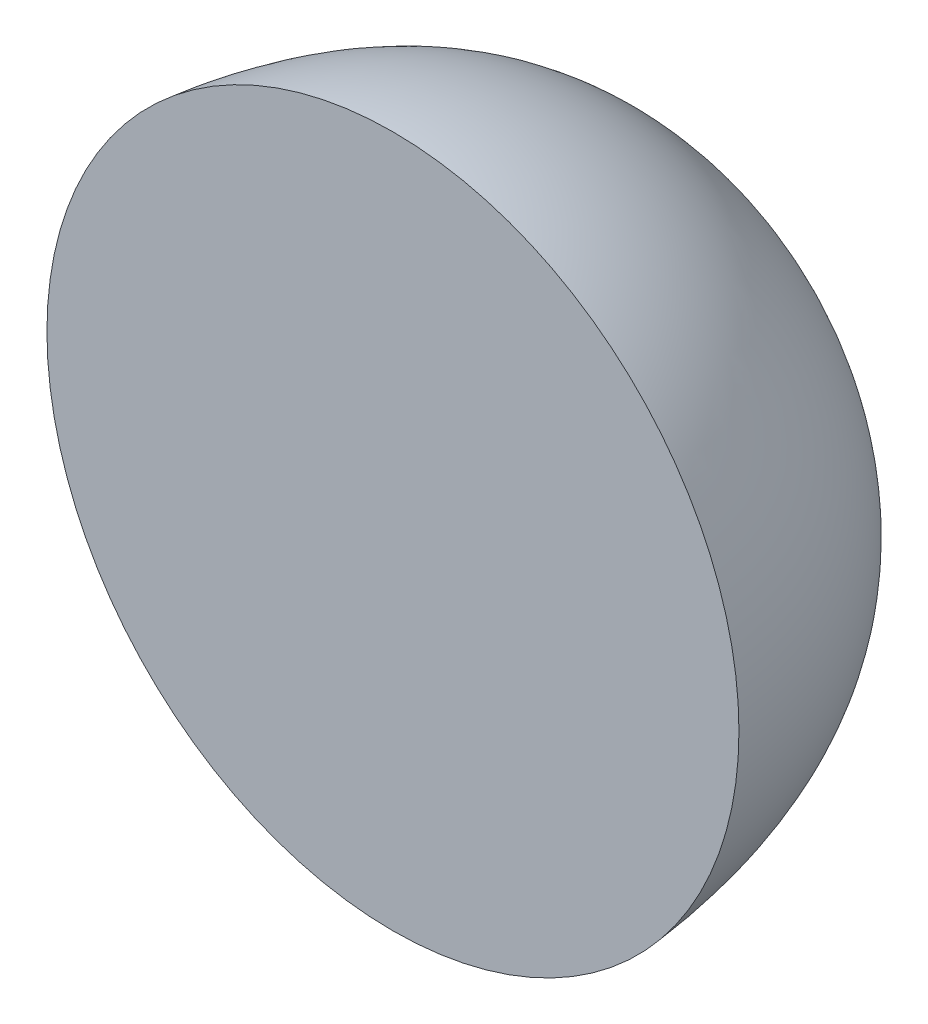
SolidWorks part; units mm, degrees
ref_plane "Front Plane" through (0, 0, 0) normal (0, 0, 1) x (1, 0, 0)
ref_plane "Top Plane" through (0, 0, 0) normal (0, 1, 0) x (1, 0, 0)
ref_plane "Right Plane" through (0, 0, 0) normal (1, 0, 0) x (0, 0, -1)
sketch "Sketch3" plane through (0, 0, 0) normal (0, 1, 0) x (1, 0, 0)
  line L0 (0, 0) -> (0, 20)
  line L2 (21.5, 0) -> (0, 0)
  spline S0 degree 2 poles (0, 20) (19.3595, 20.5347) (21.5, 0) knots 0 0 0 1 1 1
  dimension "D1" = 20
  dimension "D2" = 21.5
revolve "Revolve1" add sketch "Sketch3" angle 360 about L0
